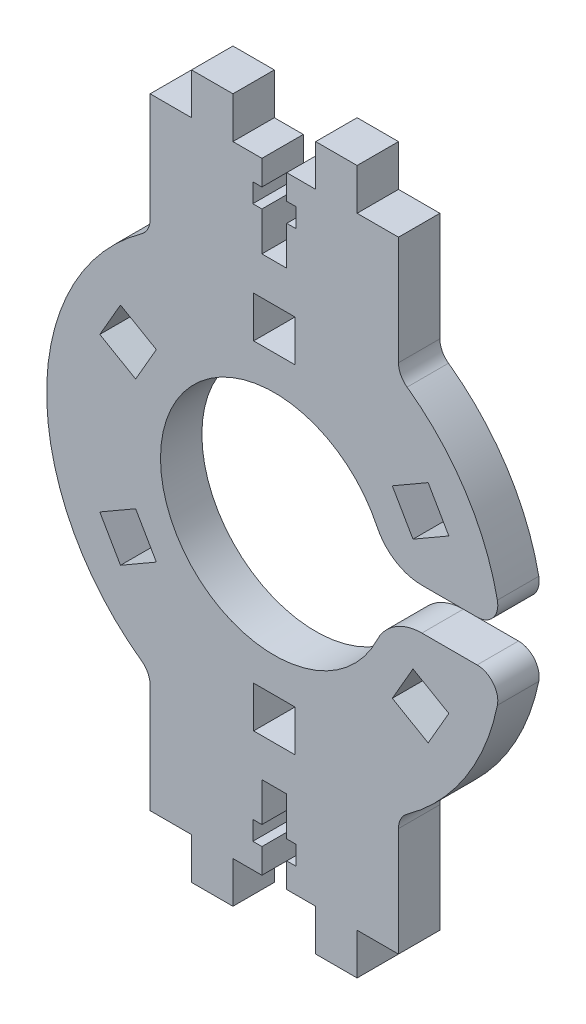
SolidWorks part; units mm, degrees
ref_plane "Plan de face" through (0, 0, 0) normal (0, 0, 1) x (1, 0, 0)
ref_plane "Plan de dessus" through (0, 0, 0) normal (0, 1, 0) x (1, 0, 0)
ref_plane "Plan de droite" through (0, 0, 0) normal (1, 0, 0) x (0, 0, -1)
sketch "Esquisse1" plane through (0, 0, 0) normal (0, 0, 1) x (1, 0, 0)
  line L0 (0, 0) -> (-5, 0)
  line L1 (-5, 0) -> (-5, -5)
  line L2 (-5, -5) -> (-10, -5)
  line L3 (-10, -5) -> (-10, 0)
  line L4 (-13.5, 3) -> (-12.4, 3)
  line L5 (-12.4, 3) -> (-12.4, 5.3)
  line L6 (-12.4, 5.3) -> (-13.5, 5.3)
  line L7 (-13.5, 5.3) -> (-13.5, 10)
  line L8 (-13.5, 10) -> (-16.5, 10)
  line L9 (-16.5, 10) -> (-16.5, 5.3)
  line L10 (-16.5, 5.3) -> (-17.6, 5.3)
  line L11 (-17.6, 5.3) -> (-17.6, 3)
  line L12 (-17.6, 3) -> (-16.5, 3)
  line L13 (-10, 0) -> (-13.5, 0)
  line L14 (-20, -5) -> (-25, -5)
  line L15 (-25, -5) -> (-25, 0)
  line L16 (-25, 0) -> (-30, 0)
  line L17 (-60, 37.5) -> (9.598, 37.5) construction
  line L18 (-16.5, 75) -> (-16.5, 72)
  line L19 (-20, 75) -> (-16.5, 75)
  line L20 (-20, 80) -> (-20, 75)
  line L21 (-13.5, 75) -> (-13.5, 72)
  line L22 (-13.5, 0) -> (-13.5, 3)
  line L23 (-25, 75) -> (-30, 75)
  line L24 (-25, 80) -> (-25, 75)
  line L25 (-20, 80) -> (-25, 80)
  line L26 (-10, 75) -> (-13.5, 75)
  line L27 (-17.6, 72) -> (-16.5, 72)
  line L28 (-17.6, 69.7) -> (-17.6, 72)
  line L29 (-16.5, 69.7) -> (-17.6, 69.7)
  line L30 (-16.5, 65) -> (-16.5, 69.7)
  line L31 (-13.5, 65) -> (-16.5, 65)
  line L32 (-20, -5) -> (-20, 0)
  line L33 (-13.5, 69.7) -> (-13.5, 65)
  line L34 (-12.4, 69.7) -> (-13.5, 69.7)
  line L35 (-12.4, 72) -> (-12.4, 69.7)
  line L36 (-20, 0) -> (-16.5, 0)
  line L37 (-16.5, 0) -> (-16.5, 3)
  line L38 (-13.5, 72) -> (-12.4, 72)
  line L39 (-10, 80) -> (-10, 75)
  line L40 (-5, 80) -> (-10, 80)
  line L41 (-5, 75) -> (-5, 80)
  line L42 (0, 75) -> (-5, 75)
  line L43 (2.8273, 40) -> (2.8273, 35) construction
  line L44 (-15, 55.4) -> (-15, 37.5) construction
  line L45 (-17.5, 60.4) -> (-12.5, 60.4)
  line L46 (-17.5, 60.4) -> (-17.5, 55.4)
  line L47 (-17.5, 55.4) -> (-12.5, 55.4)
  line L48 (-12.5, 60.4) -> (-12.5, 55.4)
  line L49 (3.582, 51.1151) -> (6.082, 46.7849)
  line L50 (3.582, 51.1151) -> (-0.7481, 48.6151)
  line L51 (-0.7481, 48.6151) -> (1.7519, 44.2849)
  line L52 (6.082, 46.7849) -> (1.7519, 44.2849)
  line L53 (6.082, 28.2151) -> (3.582, 23.8849)
  line L54 (6.082, 28.2151) -> (1.7519, 30.7151)
  line L55 (1.7519, 30.7151) -> (-0.7481, 26.3849)
  line L56 (3.582, 23.8849) -> (-0.7481, 26.3849)
  line L57 (-12.5, 14.6) -> (-17.5, 14.6)
  line L58 (-12.5, 14.6) -> (-12.5, 19.6)
  line L59 (-12.5, 19.6) -> (-17.5, 19.6)
  line L60 (-17.5, 14.6) -> (-17.5, 19.6)
  line L61 (-33.582, 23.8849) -> (-36.082, 28.2151)
  line L62 (-33.582, 23.8849) -> (-29.2519, 26.3849)
  line L63 (-29.2519, 26.3849) -> (-31.7519, 30.7151)
  line L64 (-36.082, 28.2151) -> (-31.7519, 30.7151)
  line L65 (-36.082, 46.7849) -> (-33.582, 51.1151)
  line L66 (-36.082, 46.7849) -> (-31.7519, 44.2849)
  line L67 (-31.7519, 44.2849) -> (-29.2519, 48.6151)
  line L68 (-33.582, 51.1151) -> (-29.2519, 48.6151)
  line L70 (9.4949, 40) -> (2.8273, 40)
  line L71 (2.8273, 35) -> (9.4949, 35)
  line L73 (-30, 75) -> (-30, 61.867)
  line L74 (0, 75) -> (0, 61.867)
  line L75 (0, 13.133) -> (0, 0)
  line L76 (-30, 13.133) -> (-30, 0)
  arc A0 (-31.0417, 59.8364) -> (-31.0417, 15.1636) centre (-15, 37.5) ccw
  arc A1 (-2.5886, 43.4177) -> (-2.5886, 31.5823) centre (-15, 37.5) ccw
  arc A2 (2.8273, 35) -> (-2.5886, 31.5823) centre (2.8273, 29) ccw
  arc A3 (2.8273, 40) -> (-2.5886, 43.4177) centre (2.8273, 46) cw
  arc A4 (1.0417, 15.1636) -> (11.9444, 32) centre (-15, 37.5) ccw
  arc A5 (11.9444, 43) -> (1.0417, 59.8364) centre (-15, 37.5) ccw
  arc A6 (9.4949, 40) -> (11.9444, 43) centre (9.4949, 42.5) ccw
  arc A7 (9.4949, 35) -> (11.9444, 32) centre (9.4949, 32.5) cw
  arc A8 (-30, 13.133) -> (-31.0417, 15.1636) centre (-32.5, 13.133) ccw
  arc A9 (0, 13.133) -> (1.0417, 15.1636) centre (2.5, 13.133) cw
  arc A10 (0, 61.867) -> (1.0417, 59.8364) centre (2.5, 61.867) ccw
  arc A11 (-30, 61.867) -> (-31.0417, 59.8364) centre (-32.5, 61.867) cw
  point P30 (12.3861, 40)
  point P51 (-15, 10)
  point P82 (-15, 37.5)
  point P91 (12.3861, 35)
  point P97 (0, 14.4511)
  dimension "D1" = 5
  dimension "D9" = 10
  dimension "D10" = 27.5
  dimension "D17" = 6
  dimension "D18" = 2.5
  dimension "D16" = 27.5
  dimension "D2" = 5
  dimension "D3" = 2.3
  dimension "D4" = 3
  dimension "D5" = 75
  dimension "D6" = 5
  dimension "D7" = 4.7
  dimension "D8" = 3.5
  dimension "D11" = 17.9
  dimension "D12" = 5
  dimension "D13" = 6
  dimension "D14" = 1.1
  dimension "D15" = 5
extrude "Boss.-Extru.1" add sketch "Esquisse1" along normal blind 5
